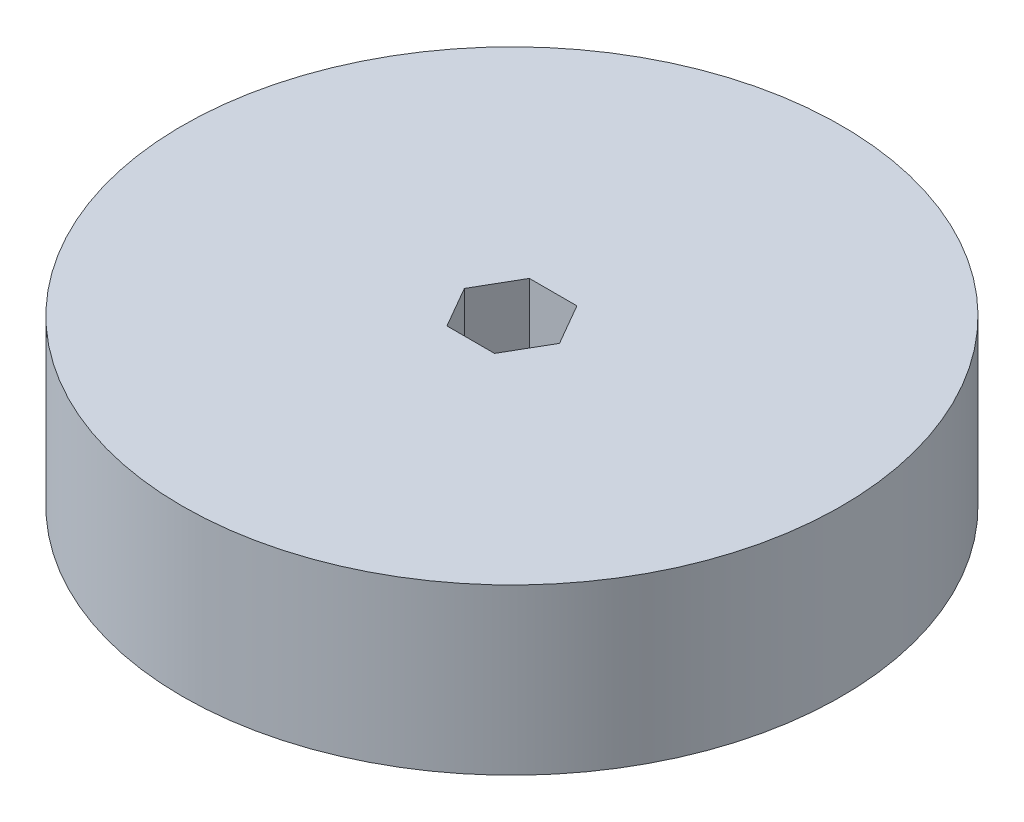
SolidWorks part; units mm, degrees
ref_plane "Front Plane" through (0, 0, 0) normal (0, 0, 1) x (1, 0, 0)
ref_plane "Top Plane" through (0, 0, 0) normal (0, 1, 0) x (1, 0, 0)
ref_plane "Right Plane" through (0, 0, 0) normal (1, 0, 0) x (0, 0, -1)
sketch "Sketch1" plane through (0, 0, 0) normal (0, 1, 0) x (1, 0, 0)
  line L1 (3.6662, -6.35) -> (7.3323, 0)
  line L2 (7.3323, 0) -> (3.6662, 6.35)
  line L3 (3.6662, 6.35) -> (-3.6662, 6.35)
  line L4 (-3.6662, 6.35) -> (-7.3323, 0)
  line L5 (-7.3323, 0) -> (-3.6662, -6.35)
  line L6 (-3.6662, -6.35) -> (3.6662, -6.35)
  circle A0 centre (0, 0) radius 50.8
  circle A1 centre (0, 0) radius 6.35 construction
  dimension "D1" = 101.6
  dimension "D2" = 12.7
extrude "Boss-Extrude1" add sketch "Sketch1" along normal blind 25.4
